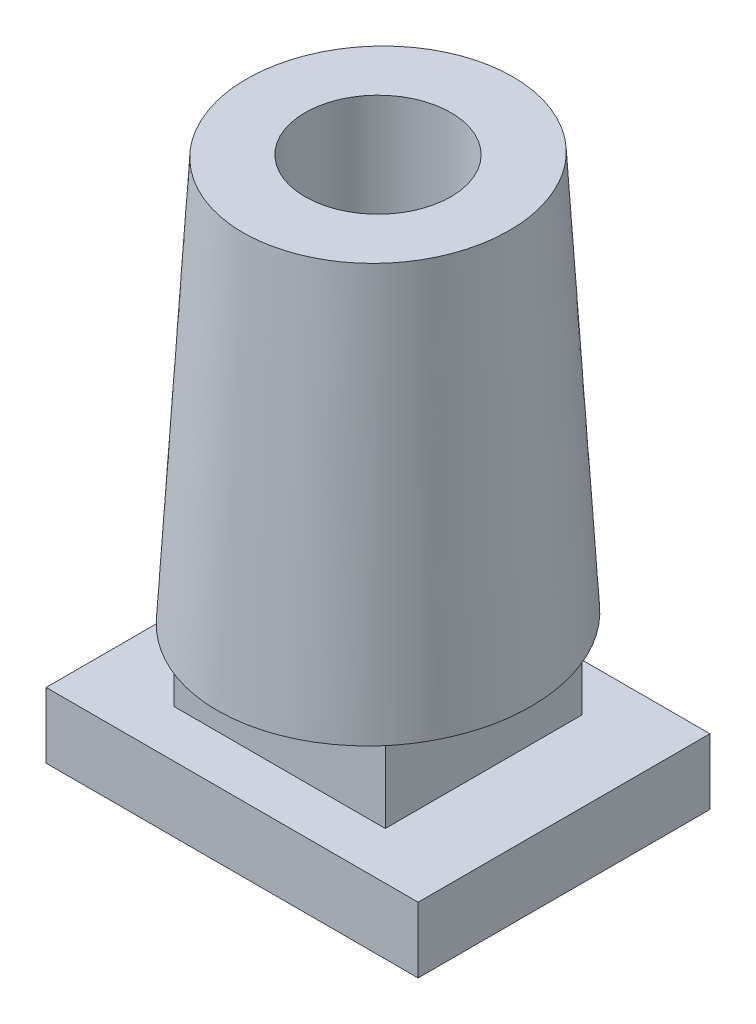
SolidWorks part; units mm, degrees
ref_plane "前视基准面" through (0, 0, 0) normal (0, 0, 1) x (1, 0, 0)
ref_plane "上视基准面" through (0, 0, 0) normal (0, 1, 0) x (1, 0, 0)
ref_plane "右视基准面" through (0, 0, 0) normal (1, 0, 0) x (0, 0, -1)
other "Configuration Table"
sketch "草图4" plane through (0, 0, 0) normal (0, 1, 0) x (1, 0, 0)
  line L1 (-5.1, -4) -> (5.1, -4)
  line L2 (-5.1, -4) -> (-5.1, 4)
  line L3 (-5.1, 4) -> (5.1, 4)
  line L4 (5.1, -4) -> (5.1, 4)
  line L5 (-5.1, -4) -> (5.1, 4) construction
  line L6 (-5.1, 4) -> (5.1, -4) construction
  point P0 (0, 0)
  dimension "D1" = 10.2
  dimension "D2" = 8
extrude "凸台-拉伸1" add sketch "草图4" along normal blind 1.8
sketch "草图5" plane through (0, 1.8, 0) normal (0, 1, 0) x (1, 0, 0)
  line L1 (-2.9, -2.7) -> (2.9, -2.7)
  line L2 (-2.9, -2.7) -> (-2.9, 2.7)
  line L3 (-2.9, 2.7) -> (2.9, 2.7)
  line L4 (2.9, -2.7) -> (2.9, 2.7)
  line L5 (-2.9, -2.7) -> (2.9, 2.7) construction
  line L6 (-2.9, 2.7) -> (2.9, -2.7) construction
  point P0 (0, 0)
  dimension "D1" = 5.4
  dimension "D2" = 5.8
extrude "凸台-拉伸2" add sketch "草图5" along normal blind 2.2
sketch "草图6" plane through (0, 4, 0) normal (0, 1, 0) x (1, 0, 0)
  ellipse E0 centre (0, 0) end of major axis (0, 4.4) minor radius 4.2
  point P1 (0, 0)
  dimension "D1" = 8.4
  dimension "D2" = 8.8
ref_plane "基准面1" through (0, 15, 0) normal (0, -1, 0) x (-1, 0, 0)
sketch "草图7" plane through (0, 15, 0) normal (0, -1, 0) x (-1, 0, 0)
  ellipse E0 centre (0, 0) end of major axis (0, -3.7) minor radius 3.6
  point P1 (0, 0)
  point P7 (0, 0)
  dimension "D1" = 7.2
  dimension "D2" = 7.4
loft "放样1" add profiles "草图7", "草图6"
sketch "草图8" plane through (0, 15, 0) normal (0, 1, 0) x (1, 0, 0)
  circle A0 centre (0, 0) radius 2
  dimension "D1" = 4
extrude "切除-拉伸1" cut sketch "草图8" against normal through all
